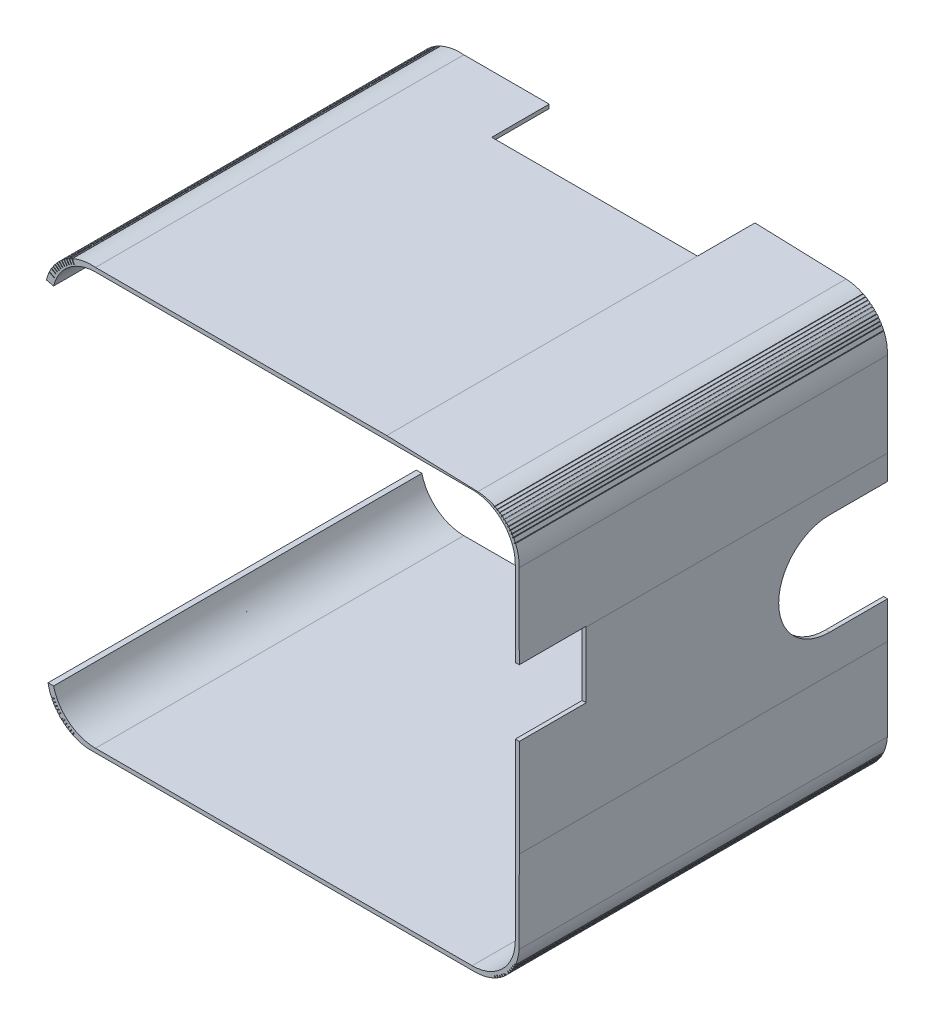
SolidWorks part; units mm, degrees
ref_plane "Front Plane" through (0, 0, 0) normal (0, 0, 1) x (1, 0, 0)
ref_plane "Top Plane" through (0, 0, 0) normal (0, 1, 0) x (1, 0, 0)
ref_plane "Right Plane" through (0, 0, 0) normal (1, 0, 0) x (0, 0, -1)
sketch "Sketch1" plane through (0, 0, 0) normal (0, 0, 1) x (1, 0, 0)
  line L0 (-55.163, -201.7371) -> (-59.0257, -201.7371)
  line L4 (-26, -224.7) -> (236, -224.7)
  line L5 (266, -194.7) -> (266, 32.2)
  line L6 (236, 62.2) -> (-26, 62.2)
  line L7 (-56, 32.2) -> (-56, -194.7)
  line L8 (-26, -224.7) -> (236, -224.7)
  line L9 (266, -194.7) -> (266, 32.2)
  line L10 (236, 62.2) -> (-26, 62.2)
  line L14 (-26, 65) -> (33.436, 65)
  line L15 (239.9524, 62.8685) -> (176.564, 65)
  line L16 (268.6486, 31.2918) -> (268.8, -27.5616)
  line L17 (268.8, -141.0448) -> (268.6902, -198.5698)
  line L18 (-31.6593, -227.5) -> (238.3459, -227.5)
  line L19 (-60.1466, 40.3291) -> (-55.1791, 39.1698)
  line L20 (268.8, -141.0448) -> (268.8, -27.5616)
  line L21 (33.436, 65) -> (176.564, 65)
  arc A4 (-56, -194.7) -> (-26, -224.7) centre (-26, -194.7) ccw
  arc A5 (236, -224.7) -> (266, -194.7) centre (236, -194.7) ccw
  arc A6 (266, 32.2) -> (236, 62.2) centre (236, 32.2) ccw
  arc A7 (-26, 62.2) -> (-56, 32.2) centre (-26, 32.2) ccw
  arc A8 (-55.163, -201.7371) -> (-26, -224.7) centre (-26, -194.7) ccw
  arc A9 (236, -224.7) -> (266, -194.7) centre (236, -194.7) ccw
  arc A10 (266, 32.2) -> (236, 62.2) centre (236, 32.2) ccw
  arc A12 (-26, 65) -> (-60.1466, 40.3291) centre (-28.7317, 32.8146) ccw
  arc A13 (268.6486, 31.2918) -> (239.9524, 62.8685) centre (238.7084, 32.9104) ccw
  arc A14 (238.3459, -227.5) -> (268.6902, -198.5698) centre (237.9517, -196.7077) ccw
  arc A15 (-59.0257, -201.7371) -> (-31.6593, -227.5) centre (-28.2098, -196.4195) ccw
  arc A16 (-26, 62.2) -> (-56, 32.2) centre (-26, 32.2) ccw construction
  arc A17 (-26, 62.2) -> (-55.1791, 39.1698) centre (-26, 32.2) ccw
  dimension "D2" = 2.8
  dimension "D3" = 2.8
  dimension "D4" = 2.8
  dimension "D8" = 2.8
  dimension "D9" = 2.8
  dimension "D5" = 2.8
  dimension "D6" = 2.8
  dimension "D7" = 2.8
  dimension "D10" = 2.8
  dimension "D1" = 0
extrude "Boss-Extrude1" add sketch "Sketch1" against normal blind 256.2
sketch "Sketch2" plane through (0, 0, -256.2) normal (0, 0, -1) x (-1, 0, 0)
  line L9 (-259.6905, -218.0981) -> (-259.5454, -217.953)
  line L14 (-259.5454, -217.953) -> (-259.2531, -218.2454)
  line L15 (-259.2531, -218.2454) -> (-259.3973, -218.3914)
  line L16 (-259.3973, -218.3914) -> (-262.6234, -221.6581)
  line L17 (-262.6234, -221.6581) -> (-262.9392, -221.3462)
  line L18 (-262.9392, -221.3462) -> (-259.6905, -218.0981)
  line L613 (-262.7689, -216.9822) -> (-261.0122, -215.4339)
  line L614 (-261.0122, -215.4339) -> (-260.8583, -215.2982)
  line L615 (-260.8583, -215.2982) -> (-260.5849, -215.6083)
  line L616 (-260.5849, -215.6083) -> (-260.738, -215.745)
  line L617 (-260.738, -215.745) -> (-262.4828, -217.3027)
  line L618 (-262.4828, -217.3027) -> (-262.7689, -216.9822)
  line L619 (-264.0898, -215.3245) -> (-262.2394, -213.8895)
  line L620 (-262.2394, -213.8895) -> (-262.0773, -213.7637)
  line L621 (-262.0773, -213.7637) -> (-261.8239, -214.0904)
  line L622 (-261.8239, -214.0904) -> (-261.9852, -214.2172)
  line L623 (-261.9852, -214.2172) -> (-263.8244, -215.6623)
  line L624 (-263.8244, -215.6623) -> (-264.0898, -215.3245)
  line L625 (-265.304, -213.5871) -> (-263.3672, -212.2711)
  line L626 (-263.3672, -212.2711) -> (-263.1975, -212.1558)
  line L627 (-263.1975, -212.1558) -> (-262.9651, -212.4977)
  line L628 (-262.9651, -212.4977) -> (-263.1341, -212.6141)
  line L629 (-263.1341, -212.6141) -> (-265.0604, -213.9409)
  line L630 (-265.0604, -213.9409) -> (-265.304, -213.5871)
  line L631 (-266.4068, -211.7769) -> (-264.3911, -210.5851)
  line L632 (-264.3911, -210.5851) -> (-264.2145, -210.4806)
  line L633 (-264.2145, -210.4806) -> (-264.0041, -210.8365)
  line L634 (-264.0041, -210.8365) -> (-264.18, -210.9421)
  line L635 (-264.18, -210.9421) -> (-266.1858, -212.1453)
  line L636 (-266.1858, -212.1453) -> (-266.4068, -211.7769)
  line L1153 (-269.8156, -211.1454) -> (-269.616, -211.5434)
  line L1154 (-265.5163, -208.9885) -> (-269.8156, -211.1454)
  line L1155 (-265.3329, -208.8965) -> (-265.5163, -208.9885)
  line L1156 (-265.1452, -209.2649) -> (-265.3329, -208.8965)
  line L1157 (-265.328, -209.3581) -> (-265.1452, -209.2649)
  line L1158 (-269.616, -211.5434) -> (-265.328, -209.3581)
  line L1159 (-267.2, -82.3121) -> (-148.4327, -82.3121) construction
  line L1162 (-269.616, 46.9193) -> (-265.328, 44.734)
  line L1163 (-265.328, 44.734) -> (-265.1452, 44.6408)
  line L1164 (-265.1452, 44.6408) -> (-265.3329, 44.2724)
  line L1165 (-265.3329, 44.2724) -> (-265.5163, 44.3644)
  line L1166 (-265.5163, 44.3644) -> (-269.8156, 46.5213)
  line L1167 (-269.8156, 46.5213) -> (-269.616, 46.9193)
  line L1168 (-260.2101, 57.7017) -> (-260.5392, 57.4151)
  line L1169 (-257.9684, 55.1267) -> (-260.2101, 57.7017)
  line L1170 (-257.8336, 54.9719) -> (-257.9684, 55.1267)
  line L1171 (-258.1437, 54.6985) -> (-257.8336, 54.9719)
  line L1172 (-258.2795, 54.8524) -> (-258.1437, 54.6985)
  line L1173 (-260.5392, 57.4151) -> (-258.2795, 54.8524)
  line L1174 (-258.7827, 59.4311) -> (-259.1313, 59.1642)
  line L1175 (-256.4569, 56.3937) -> (-258.7827, 59.4311)
  line L1176 (-256.3322, 56.2308) -> (-256.4569, 56.3937)
  line L1177 (-256.6588, 55.9774) -> (-256.3322, 56.2308)
  line L1178 (-256.7846, 56.1395) -> (-256.6588, 55.9774)
  line L1179 (-259.1313, 59.1642) -> (-256.7846, 56.1395)
  line L1180 (-256.9038, 60.5981) -> (-257.2675, 60.3543)
  line L1181 (-254.8689, 57.5633) -> (-256.9038, 60.5981)
  line L1182 (-254.7546, 57.3929) -> (-254.8689, 57.5633)
  line L1183 (-255.0966, 57.1605) -> (-254.7546, 57.3929)
  line L1184 (-255.2119, 57.3302) -> (-255.0966, 57.1605)
  line L1185 (-257.2675, 60.3543) -> (-255.2119, 57.3302)
  line L1186 (-254.8455, 61.4351) -> (-255.2216, 61.2159)
  line L1187 (-253.2106, 58.6309) -> (-254.8455, 61.4351)
  line L1188 (-253.1073, 58.4536) -> (-253.2106, 58.6309)
  line L1189 (-253.4631, 58.2431) -> (-253.1073, 58.4536)
  line L1190 (-253.5676, 58.4198) -> (-253.4631, 58.2431)
  line L1191 (-255.2216, 61.2159) -> (-253.5676, 58.4198)
  line L1192 (-253.1072, 62.8188) -> (-253.4984, 62.6226)
  line L1193 (-251.4885, 59.5922) -> (-253.1072, 62.8188)
  line L1194 (-251.3965, 59.4088) -> (-251.4885, 59.5922)
  line L1195 (-251.7649, 59.2211) -> (-251.3965, 59.4088)
  line L1196 (-251.8581, 59.4039) -> (-251.7649, 59.2211)
  line L1197 (-253.4984, 62.6226) -> (-251.8581, 59.4039)
  line L1198 (-267.7315, 49.6483) -> (-267.9583, 49.2702)
  line L1199 (-264.18, 47.518) -> (-267.7315, 49.6483)
  line L1200 (-264.0041, 47.4124) -> (-264.18, 47.518)
  line L1201 (-264.2145, 47.0565) -> (-264.0041, 47.4124)
  line L1202 (-264.3911, 47.161) -> (-264.2145, 47.0565)
  line L1203 (-267.9583, 49.2702) -> (-264.3911, 47.161)
  line L1204 (-267.2251, 52.0078) -> (-267.4783, 51.6403)
  line L1205 (-263.1341, 49.19) -> (-267.2251, 52.0078)
  line L1206 (-262.9651, 49.0736) -> (-263.1341, 49.19)
  line L1207 (-263.1975, 48.7317) -> (-262.9651, 49.0736)
  line L1208 (-263.3672, 48.847) -> (-263.1975, 48.7317)
  line L1209 (-267.4783, 51.6403) -> (-263.3672, 48.847)
  line L1210 (-265.2803, 53.3822) -> (-265.553, 53.0351)
  line L1211 (-261.9852, 50.7931) -> (-265.2803, 53.3822)
  line L1212 (-261.8239, 50.6663) -> (-261.9852, 50.7931)
  line L1213 (-262.0773, 50.3396) -> (-261.8239, 50.6663)
  line L1214 (-262.2394, 50.4654) -> (-262.0773, 50.3396)
  line L1215 (-265.553, 53.0351) -> (-262.2394, 50.4654)
  line L1216 (-264.0307, 55.2605) -> (-264.3255, 54.9303)
  line L1217 (-260.738, 52.3209) -> (-264.0307, 55.2605)
  line L1218 (-260.5849, 52.1842) -> (-260.738, 52.3209)
  line L1219 (-260.8583, 51.8741) -> (-260.5849, 52.1842)
  line L1220 (-261.0122, 52.0098) -> (-260.8583, 51.8741)
  line L1221 (-264.3255, 54.9303) -> (-261.0122, 52.0098)
  line L1222 (-262.9392, 56.7221) -> (-259.6905, 53.474)
  line L1223 (-262.6234, 57.034) -> (-262.9392, 56.7221)
  line L1224 (-259.3973, 53.7673) -> (-262.6234, 57.034)
  line L1225 (-259.2531, 53.6213) -> (-259.3973, 53.7673)
  line L1226 (-259.5454, 53.3289) -> (-259.2531, 53.6213)
  line L1227 (-259.6905, 53.474) -> (-259.5454, 53.3289)
  line L1228 (-105.3248, 62.2) -> (-105.3248, 0) construction
  line L1232 (58.9663, -211.5434) -> (54.6784, -209.3581)
  line L1233 (54.6784, -209.3581) -> (54.4955, -209.2649)
  line L1234 (54.4955, -209.2649) -> (54.6833, -208.8965)
  line L1235 (54.6833, -208.8965) -> (54.8667, -208.9885)
  line L1236 (54.8667, -208.9885) -> (59.1659, -211.1454)
  line L1237 (59.1659, -211.1454) -> (58.9663, -211.5434)
  line L1238 (48.8545, -220.3149) -> (49.1785, -220.0329)
  line L1239 (47.3187, -218.5508) -> (48.8545, -220.3149)
  line L1240 (47.184, -218.3961) -> (47.3187, -218.5508)
  line L1241 (47.4941, -218.1226) -> (47.184, -218.3961)
  line L1242 (47.6298, -218.2765) -> (47.4941, -218.1226)
  line L1243 (49.1785, -220.0329) -> (47.6298, -218.2765)
  line L1244 (47.2292, -221.6749) -> (47.5703, -221.4137)
  line L1245 (45.8072, -219.8178) -> (47.2292, -221.6749)
  line L1246 (45.6825, -219.6549) -> (45.8072, -219.8178)
  line L1247 (46.0092, -219.4015) -> (45.6825, -219.6549)
  line L1248 (46.135, -219.5636) -> (46.0092, -219.4015)
  line L1249 (47.5703, -221.4137) -> (46.135, -219.5636)
  line L1250 (45.5218, -222.9301) -> (45.8786, -222.6909)
  line L1251 (44.2192, -220.9874) -> (45.5218, -222.9301)
  line L1252 (44.105, -220.817) -> (44.2192, -220.9874)
  line L1253 (44.4469, -220.5846) -> (44.105, -220.817)
  line L1254 (44.5623, -220.7543) -> (44.4469, -220.5846)
  line L1255 (45.8786, -222.6909) -> (44.5623, -220.7543)
  line L1256 (43.739, -224.0756) -> (44.1101, -223.8593)
  line L1257 (42.5609, -222.055) -> (43.739, -224.0756)
  line L1258 (42.4576, -221.8777) -> (42.5609, -222.055)
  line L1259 (42.8134, -221.6672) -> (42.4576, -221.8777)
  line L1260 (42.9179, -221.8439) -> (42.8134, -221.6672)
  line L1261 (44.1101, -223.8593) -> (42.9179, -221.8439)
  line L1262 (41.8877, -225.107) -> (42.2717, -224.9143)
  line L1263 (40.8388, -223.0163) -> (41.8877, -225.107)
  line L1264 (40.7468, -222.8329) -> (40.8388, -223.0163)
  line L1265 (41.1152, -222.6452) -> (40.7468, -222.8329)
  line L1266 (41.2084, -222.828) -> (41.1152, -222.6452)
  line L1267 (42.2717, -224.9143) -> (41.2084, -222.828)
  line L1268 (55.5361, -212.1453) -> (55.7571, -211.7769)
  line L1269 (53.5303, -210.9421) -> (55.5361, -212.1453)
  line L1270 (53.3544, -210.8365) -> (53.5303, -210.9421)
  line L1271 (53.5648, -210.4806) -> (53.3544, -210.8365)
  line L1272 (53.7415, -210.5851) -> (53.5648, -210.4806)
  line L1273 (55.7571, -211.7769) -> (53.7415, -210.5851)
  line L1274 (54.4107, -213.9409) -> (54.6544, -213.5871)
  line L1275 (52.4844, -212.6141) -> (54.4107, -213.9409)
  line L1276 (52.3154, -212.4977) -> (52.4844, -212.6141)
  line L1277 (52.5478, -212.1558) -> (52.3154, -212.4977)
  line L1278 (52.7175, -212.2711) -> (52.5478, -212.1558)
  line L1279 (54.6544, -213.5871) -> (52.7175, -212.2711)
  line L1280 (53.1747, -215.6623) -> (53.4401, -215.3245)
  line L1281 (51.3355, -214.2172) -> (53.1747, -215.6623)
  line L1282 (51.1742, -214.0904) -> (51.3355, -214.2172)
  line L1283 (51.4276, -213.7637) -> (51.1742, -214.0904)
  line L1284 (51.5897, -213.8895) -> (51.4276, -213.7637)
  line L1285 (53.4401, -215.3245) -> (51.5897, -213.8895)
  line L1286 (51.8331, -217.3027) -> (52.1192, -216.9822)
  line L1287 (50.0883, -215.745) -> (51.8331, -217.3027)
  line L1288 (49.9352, -215.6083) -> (50.0883, -215.745)
  line L1289 (50.2086, -215.2982) -> (49.9352, -215.6083)
  line L1290 (50.3626, -215.4339) -> (50.2086, -215.2982)
  line L1291 (52.1192, -216.9822) -> (50.3626, -215.4339)
  line L1292 (52.2895, -221.3462) -> (49.0408, -218.0981)
  line L1293 (51.9737, -221.6581) -> (52.2895, -221.3462)
  line L1294 (48.7476, -218.3914) -> (51.9737, -221.6581)
  line L1295 (48.6034, -218.2454) -> (48.7476, -218.3914)
  line L1296 (48.8957, -217.953) -> (48.6034, -218.2454)
  line L1297 (49.0408, -218.0981) -> (48.8957, -217.953)
  line L1298 (25.3503, 30.0759) -> (48.8951, 53.6207) construction
  line L1299 (49.0408, 53.474) -> (48.8957, 53.3289)
  line L1300 (48.8957, 53.3289) -> (48.6034, 53.6213)
  line L1301 (48.6034, 53.6213) -> (48.7476, 53.7673)
  line L1302 (48.7476, 53.7673) -> (51.9737, 57.034)
  line L1303 (51.9737, 57.034) -> (52.2895, 56.7221)
  line L1304 (52.2895, 56.7221) -> (49.0408, 53.474)
  line L1305 (53.6759, 54.9303) -> (50.3626, 52.0098)
  line L1306 (50.3626, 52.0098) -> (50.2086, 51.8741)
  line L1307 (50.2086, 51.8741) -> (49.9352, 52.1842)
  line L1308 (49.9352, 52.1842) -> (50.0883, 52.3209)
  line L1309 (50.0883, 52.3209) -> (53.381, 55.2605)
  line L1310 (53.381, 55.2605) -> (53.6759, 54.9303)
  line L1311 (54.9033, 53.0351) -> (51.5897, 50.4654)
  line L1312 (51.5897, 50.4654) -> (51.4276, 50.3396)
  line L1313 (51.4276, 50.3396) -> (51.1742, 50.6663)
  line L1314 (51.1742, 50.6663) -> (51.3355, 50.7931)
  line L1315 (51.3355, 50.7931) -> (54.6307, 53.3822)
  line L1316 (54.6307, 53.3822) -> (54.9033, 53.0351)
  line L1317 (56.8286, 51.6403) -> (52.7175, 48.847)
  line L1318 (52.7175, 48.847) -> (52.5478, 48.7317)
  line L1319 (52.5478, 48.7317) -> (52.3154, 49.0736)
  line L1320 (52.3154, 49.0736) -> (52.4844, 49.19)
  line L1321 (52.4844, 49.19) -> (56.5755, 52.0078)
  line L1322 (56.5755, 52.0078) -> (56.8286, 51.6403)
  line L1323 (57.3087, 49.2702) -> (53.7415, 47.161)
  line L1324 (53.7415, 47.161) -> (53.5648, 47.0565)
  line L1325 (53.5648, 47.0565) -> (53.3544, 47.4124)
  line L1326 (53.3544, 47.4124) -> (53.5303, 47.518)
  line L1327 (53.5303, 47.518) -> (57.0818, 49.6483)
  line L1328 (57.0818, 49.6483) -> (57.3087, 49.2702)
  line L1329 (42.8487, 62.6226) -> (41.2084, 59.4039)
  line L1330 (41.2084, 59.4039) -> (41.1152, 59.2211)
  line L1331 (41.1152, 59.2211) -> (40.7468, 59.4088)
  line L1332 (40.7468, 59.4088) -> (40.8388, 59.5922)
  line L1333 (40.8388, 59.5922) -> (42.4576, 62.8188)
  line L1334 (42.4576, 62.8188) -> (42.8487, 62.6226)
  line L1335 (44.5719, 61.2159) -> (42.9179, 58.4198)
  line L1336 (42.9179, 58.4198) -> (42.8134, 58.2431)
  line L1337 (42.8134, 58.2431) -> (42.4576, 58.4536)
  line L1338 (42.4576, 58.4536) -> (42.5609, 58.6309)
  line L1339 (42.5609, 58.6309) -> (44.1958, 61.4351)
  line L1340 (44.1958, 61.4351) -> (44.5719, 61.2159)
  line L1341 (46.6178, 60.3543) -> (44.5623, 57.3302)
  line L1342 (44.5623, 57.3302) -> (44.4469, 57.1605)
  line L1343 (44.4469, 57.1605) -> (44.105, 57.3929)
  line L1344 (44.105, 57.3929) -> (44.2192, 57.5633)
  line L1345 (44.2192, 57.5633) -> (46.2541, 60.5981)
  line L1346 (46.2541, 60.5981) -> (46.6178, 60.3543)
  line L1347 (48.4816, 59.1642) -> (46.135, 56.1395)
  line L1348 (46.135, 56.1395) -> (46.0092, 55.9774)
  line L1349 (46.0092, 55.9774) -> (45.6825, 56.2308)
  line L1350 (45.6825, 56.2308) -> (45.8072, 56.3937)
  line L1351 (45.8072, 56.3937) -> (48.133, 59.4311)
  line L1352 (48.133, 59.4311) -> (48.4816, 59.1642)
  line L1353 (49.8895, 57.4151) -> (47.6298, 54.8524)
  line L1354 (47.6298, 54.8524) -> (47.4941, 54.6985)
  line L1355 (47.4941, 54.6985) -> (47.184, 54.9719)
  line L1356 (47.184, 54.9719) -> (47.3187, 55.1267)
  line L1357 (47.3187, 55.1267) -> (49.5604, 57.7017)
  line L1358 (49.5604, 57.7017) -> (49.8895, 57.4151)
  line L1359 (59.1659, 46.5213) -> (58.9663, 46.9193)
  line L1360 (54.8667, 44.3644) -> (59.1659, 46.5213)
  line L1361 (54.6833, 44.2724) -> (54.8667, 44.3644)
  line L1362 (54.4955, 44.6408) -> (54.6833, 44.2724)
  line L1363 (54.6784, 44.734) -> (54.4955, 44.6408)
  line L1364 (58.9663, 46.9193) -> (54.6784, 44.734)
  line L1386 (-252.9213, -224.9143) -> (-251.8581, -222.828)
  line L1387 (-251.8581, -222.828) -> (-251.7649, -222.6452)
  line L1388 (-251.7649, -222.6452) -> (-251.3965, -222.8329)
  line L1389 (-251.3965, -222.8329) -> (-251.4885, -223.0163)
  line L1390 (-251.4885, -223.0163) -> (-252.5374, -225.107)
  line L1391 (-252.5374, -225.107) -> (-252.9213, -224.9143)
  line L1392 (-254.7598, -223.8593) -> (-253.5676, -221.8439)
  line L1393 (-253.5676, -221.8439) -> (-253.4631, -221.6672)
  line L1394 (-253.4631, -221.6672) -> (-253.1073, -221.8777)
  line L1395 (-253.1073, -221.8777) -> (-253.2106, -222.055)
  line L1396 (-253.2106, -222.055) -> (-254.3886, -224.0756)
  line L1397 (-254.3886, -224.0756) -> (-254.7598, -223.8593)
  line L1398 (-256.5283, -222.6909) -> (-255.2119, -220.7543)
  line L1399 (-255.2119, -220.7543) -> (-255.0966, -220.5846)
  line L1400 (-255.0966, -220.5846) -> (-254.7546, -220.817)
  line L1401 (-254.7546, -220.817) -> (-254.8689, -220.9874)
  line L1402 (-254.8689, -220.9874) -> (-256.1715, -222.9301)
  line L1403 (-256.1715, -222.9301) -> (-256.5283, -222.6909)
  line L1404 (-258.22, -221.4137) -> (-256.7846, -219.5636)
  line L1405 (-256.7846, -219.5636) -> (-256.6588, -219.4015)
  line L1406 (-256.6588, -219.4015) -> (-256.3322, -219.6549)
  line L1407 (-256.3322, -219.6549) -> (-256.4569, -219.8178)
  line L1408 (-256.4569, -219.8178) -> (-257.8789, -221.6749)
  line L1409 (-257.8789, -221.6749) -> (-258.22, -221.4137)
  line L1410 (-259.8282, -220.0329) -> (-258.2795, -218.2765)
  line L1411 (-258.2795, -218.2765) -> (-258.1437, -218.1226)
  line L1412 (-258.1437, -218.1226) -> (-257.8336, -218.3961)
  line L1413 (-257.8336, -218.3961) -> (-257.9684, -218.5508)
  line L1414 (-257.9684, -218.5508) -> (-259.5042, -220.3149)
  line L1415 (-259.5042, -220.3149) -> (-259.8282, -220.0329)
  circle A0 centre (-236, -194.7) radius 33.2974 construction
  circle A3 centre (-236, 30.0759) radius 33.2974 construction
  circle A4 centre (25.3503, -194.7) radius 33.2974 construction
  circle A5 centre (25.3503, 30.0759) radius 33.2974 construction
  point P825 (-237.0543, -195.137)
sketch "Sketch3" plane through (2.3826, 70.8569, 0) normal (0.0336, 0.9994, 0) x (0.9994, -0.0336, 0)
  line L0 (31.2327, 256.2) -> (31.2327, 216.2)
  line L1 (237.7041, 256.2) -> (174.2798, 256.2) construction
  line L2 (31.2327, 255) -> (31.2327, 258.8) construction
  line L3 (174.2798, 256.2) -> (174.2798, 216.2)
  line L4 (174.2798, 255) -> (174.2798, 258.8) construction
  line L5 (174.2798, 216.2) -> (31.2327, 216.2)
  line L6 (31.2327, 256.2) -> (174.2798, 256.2)
  dimension "D1" = 40
  dimension "D2" = 40
extrude "Cut-Extrude2" cut sketch "Sketch3" against normal blind 10
sketch "Sketch4" plane through (268.8, 0, 0) normal (1, 0, 0) x (0, 0, -1)
  line L0 (314.8786, -80) -> (320.3042, -80) construction
  line L1 (215.8035, -115.3374) -> (256.2, -115.3374)
  line L2 (256.2, -141.0448) -> (256.2, -27.5616) construction
  line L3 (215.8035, -44.6626) -> (256.2, -44.6626)
  line L4 (256.2, -44.6626) -> (256.2, -115.3374)
  arc A0 (215.8035, -44.6626) -> (215.8035, -115.3374) centre (215.8035, -80) ccw
  dimension "D1" = 70.6749
  dimension "D2" = 40.3965
extrude "Cut-Extrude3" cut sketch "Sketch4" against normal blind 10 contours L4 L1 A0 L3
sketch "Sketch5" plane through (268.8, 0, 0) normal (1, 0, 0) x (0, 0, -1)
  line L0 (0, -141.0448) -> (0, -27.5616) construction
  line L1 (0, -73.1734) -> (46.5547, -73.1734)
  line L2 (0, -73.1734) -> (0, -27.0188)
  line L3 (0, -27.0188) -> (46.5547, -27.0188)
  line L4 (46.5547, -73.1734) -> (46.5547, -27.0188)
extrude "Cut-Extrude4" cut sketch "Sketch5" against normal blind 10
extrude "Cut-Extrude5" cut sketch "Sketch2" against normal through all
